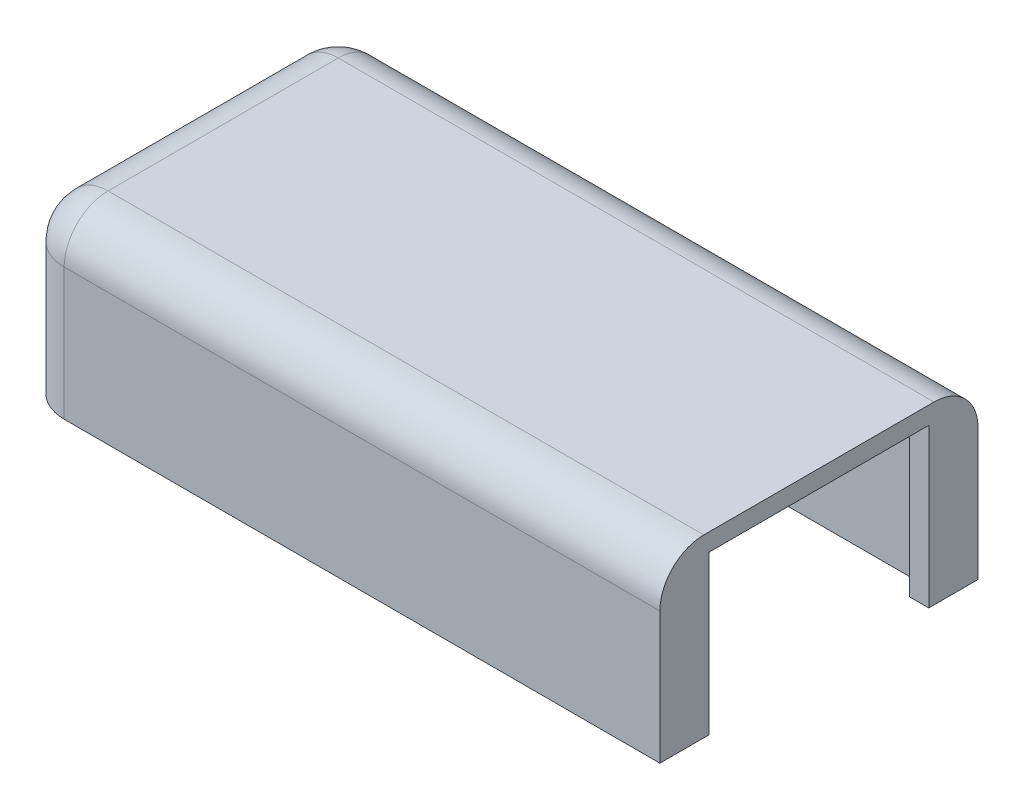
SolidWorks part; units mm, degrees
ref_plane "前视基准面" through (0, 0, 0) normal (0, 0, 1) x (1, 0, 0)
ref_plane "上视基准面" through (0, 0, 0) normal (0, 1, 0) x (1, 0, 0)
ref_plane "右视基准面" through (0, 0, 0) normal (1, 0, 0) x (0, 0, -1)
other "Configuration Table"
sketch "草图1" plane through (0, 0, 0) normal (0, 1, 0) x (1, 0, 0)
  line L1 (0, 29) -> (65, 29)
  line L2 (0, 29) -> (0, 0)
  line L3 (0, 0) -> (65, 0)
  line L4 (65, 29) -> (65, 0)
  dimension "D1" = 65
  dimension "D2" = 29
extrude "拉伸-薄壁1" add sketch "草图1" along normal blind 20 thin thin type one direction wall 3.6
sketch "草图2" plane through (65, 0, 0) normal (-1, 0, 0) x (0, 0, 1)
  line L1 (-29, 20) -> (0, 20)
  line L2 (-29, 20) -> (-29, 0)
  line L3 (-29, 0) -> (0, 0)
  line L4 (0, 20) -> (0, 0)
extrude "切除-拉伸1" cut sketch "草图2" against normal blind 3.6
sketch "草图3" plane through (68.6, 0, 0) normal (1, 0, 0) x (0, 0, -1)
  line L1 (-3.6, 20) -> (0, 20)
  line L2 (-3.6, 20) -> (-3.6, 0)
  line L3 (-3.6, 0) -> (0, 0)
  line L4 (0, 20) -> (0, 0)
  line L5 (29, 20) -> (32.6, 20)
  line L6 (29, 20) -> (29, 0)
  line L7 (29, 0) -> (32.6, 0)
  line L8 (32.6, 20) -> (32.6, 0)
extrude "凸台-拉伸1" add sketch "草图3" along normal blind 0.6
sketch "草图4" plane through (0, 0, 0) normal (0, 0, -1) x (-1, 0, 0)
  line L1 (-69.2, 20) -> (-67, 20)
  line L2 (-69.2, 20) -> (-69.2, 0)
  line L3 (-69.2, 0) -> (-67, 0)
  line L4 (-67, 20) -> (-67, 0)
  point P7 (0, 0)
extrude "凸台-拉伸2" add sketch "草图4" along normal blind 2
sketch "草图5" plane through (0, 0, -29) normal (0, 0, 1) x (1, 0, 0)
  line L1 (69.2, 20) -> (67, 20)
  line L2 (69.2, 20) -> (69.2, 0)
  line L3 (69.2, 0) -> (67, 0)
  line L4 (67, 20) -> (67, 0)
extrude "凸台-拉伸3" add sketch "草图5" along normal blind 2
sketch "草图6" plane through (0, 20, 0) normal (0, 1, 0) x (1, 0, 0)
  line L1 (-3.6, 32.6) -> (69.2, 32.6)
  line L2 (-3.6, 32.6) -> (-3.6, -3.6)
  line L3 (-3.6, -3.6) -> (69.2, -3.6)
  line L4 (69.2, 32.6) -> (69.2, -3.6)
extrude "凸台-拉伸4" add sketch "草图6" against normal blind 2
fillet "圆角1" radius 5 1 edges at (32.8, 20, -32.6)
fillet "圆角2" radius 5 1 edges at (32.8, 20, 3.6)
fillet "圆角3" radius 5 5 edges at (-3.6, 7.5, -32.6) (-3.6, 18.5355, -31.1355) (-3.6, 7.5, 3.6) (-3.6, 18.5355, 2.1355) (-3.6, 20, -14.5)
